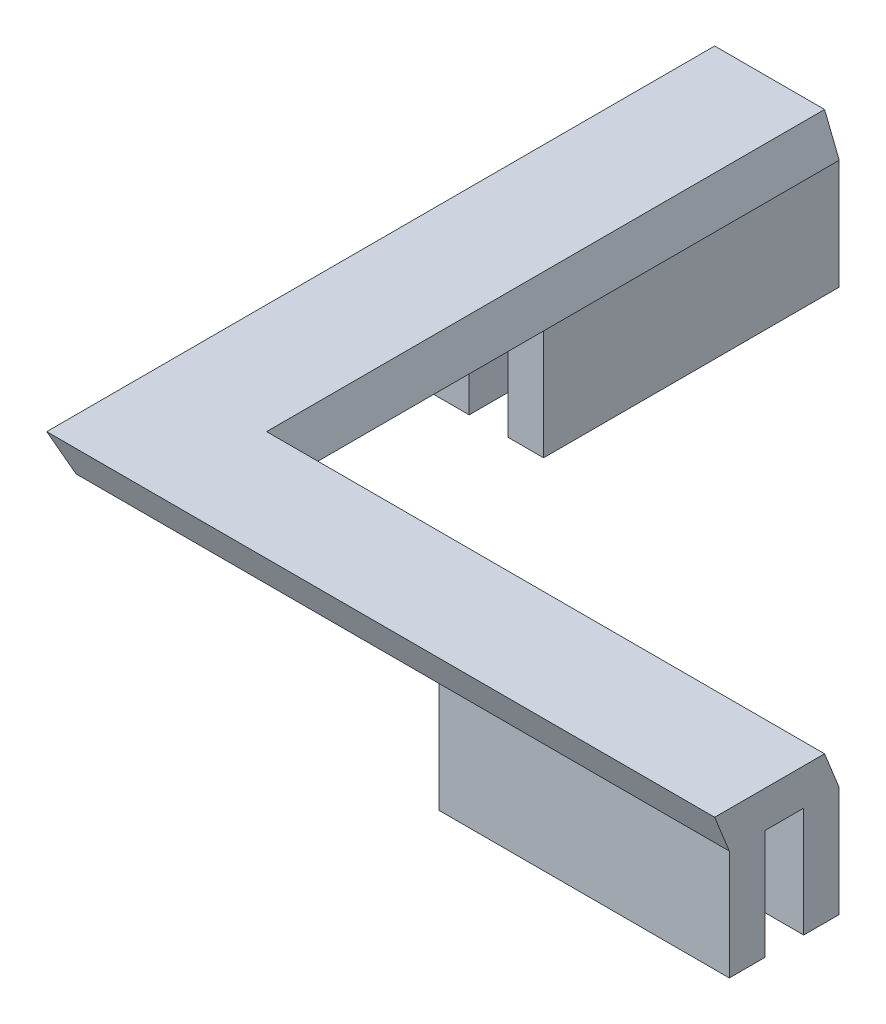
SolidWorks part; units mm, degrees
ref_plane "Front Plane" through (0, 0, 0) normal (0, 0, 1) x (1, 0, 0)
ref_plane "Top Plane" through (0, 0, 0) normal (0, 1, 0) x (1, 0, 0)
ref_plane "Right Plane" through (0, 0, 0) normal (1, 0, 0) x (0, 0, -1)
sketch "Sketch1" plane through (0, 0, 0) normal (0, 1, 0) x (1, 0, 0)
  line L1 (0, 0) -> (227.33, 0)
  line L2 (0, 0) -> (0, 225.552)
  line L3 (0, 225.552) -> (227.33, 225.552)
  line L4 (227.33, 0) -> (227.33, 225.552)
  dimension "D1" = 227.33
  dimension "D2" = 225.552
ref_plane "Plane1" through (0, 127, 0) normal (0, 1, 0) x (1, 0, 0)
sketch "Sketch2" plane through (0, 127, 0) normal (0, 1, 0) x (1, 0, 0)
  line L8 (-50.8, -50.8) -> (278.13, -50.8)
  line L9 (278.13, -50.8) -> (278.13, 276.352)
  line L10 (278.13, 276.352) -> (-50.8, 276.352)
  line L11 (-50.8, 276.352) -> (-50.8, -50.8)
  line L12 (-50.8, -50.8) -> (278.13, -50.8)
  line L13 (278.13, -50.8) -> (278.13, 276.352)
  line L14 (278.13, 276.352) -> (-50.8, 276.352)
  line L15 (-50.8, 276.352) -> (-50.8, -50.8)
  dimension "D1" = 50.8
loft "Loft1" add profiles "Sketch2" section "Sketch2" section "Sketch1"
sketch "Sketch3" plane through (0, 127, 0) normal (0, 1, 0) x (1, 0, 0)
  line L8 (-31.75, 257.302) -> (-31.75, -31.75)
  line L9 (-31.75, -31.75) -> (259.08, -31.75)
  line L10 (259.08, -31.75) -> (259.08, 257.302)
  line L11 (259.08, 257.302) -> (-31.75, 257.302)
  line L12 (-31.75, 257.302) -> (-31.75, -31.75)
  line L13 (-31.75, -31.75) -> (259.08, -31.75)
  line L14 (259.08, -31.75) -> (259.08, 257.302)
  line L15 (259.08, 257.302) -> (-31.75, 257.302)
  dimension "D1" = 19.05
sketch "Sketch4" plane through (0, 0, 0) normal (0, -1, 0) x (1, 0, 0)
  line L8 (208.28, -19.05) -> (19.05, -19.05)
  line L9 (19.05, -19.05) -> (19.05, -206.502)
  line L10 (19.05, -206.502) -> (208.28, -206.502)
  line L11 (208.28, -206.502) -> (208.28, -19.05)
  line L12 (208.28, -19.05) -> (19.05, -19.05)
  line L13 (19.05, -19.05) -> (19.05, -206.502)
  line L14 (19.05, -206.502) -> (208.28, -206.502)
  line L15 (208.28, -206.502) -> (208.28, -19.05)
  dimension "D1" = 19.05
loft "Cut-Loft3" cut profiles "Sketch3" section "Sketch4" section "Sketch3"
sketch "Sketch5" plane through (0, 0, 0) normal (0, -1, 0) x (1, 0, 0)
  line L0 (0, -61.976) -> (6.1595, -61.976)
  line L5 (0, -61.976) -> (0, -163.576)
  line L6 (0, 0) -> (0, -225.552) construction
  line L7 (6.1595, -61.976) -> (6.1595, -163.576)
  line L8 (6.1595, -163.576) -> (0, -163.576)
  line L9 (19.05, -61.976) -> (19.05, -163.576)
  line L10 (19.05, -19.05) -> (19.05, -206.502) construction
  line L11 (19.05, -61.976) -> (12.8905, -61.976)
  line L12 (12.8905, -61.976) -> (12.8905, -163.576)
  line L13 (12.8905, -163.576) -> (19.05, -163.576)
  line L14 (19.05, -19.05) -> (208.28, -206.502) construction
  line L15 (164.465, -6.1595) -> (62.865, -6.1595)
  line L16 (164.465, 0) -> (62.865, 0)
  line L17 (164.465, 0) -> (164.465, -6.1595)
  line L18 (62.865, -6.1595) -> (62.865, 0)
  line L19 (164.465, -12.8905) -> (62.865, -12.8905)
  line L20 (164.465, -19.05) -> (62.865, -19.05)
  line L21 (164.465, -19.05) -> (164.465, -12.8905)
  line L22 (62.865, -12.8905) -> (62.865, -19.05)
  line L23 (220.2815, -164.465) -> (220.2815, -62.865)
  line L24 (226.441, -164.465) -> (226.441, -62.865)
  line L25 (226.441, -164.465) -> (220.2815, -164.465)
  line L26 (220.2815, -62.865) -> (226.441, -62.865)
  line L27 (213.5505, -164.465) -> (213.5505, -62.865)
  line L28 (207.391, -164.465) -> (207.391, -62.865)
  line L29 (207.391, -164.465) -> (213.5505, -164.465)
  line L30 (213.5505, -62.865) -> (207.391, -62.865)
  line L31 (61.976, -220.2815) -> (163.576, -220.2815)
  line L32 (61.976, -226.441) -> (163.576, -226.441)
  line L33 (61.976, -226.441) -> (61.976, -220.2815)
  line L34 (163.576, -220.2815) -> (163.576, -226.441)
  line L35 (61.976, -213.5505) -> (163.576, -213.5505)
  line L36 (61.976, -207.391) -> (163.576, -207.391)
  line L37 (61.976, -207.391) -> (61.976, -213.5505)
  line L38 (163.576, -213.5505) -> (163.576, -207.391)
  line L39 (0, 0) -> (227.33, 0) construction
  point P5 (0, -112.776)
  point P12 (19.05, -112.776)
  point P14 (113.665, -112.776)
  point P46 (113.2205, -113.2205)
  dimension "D1" = 101.6
  dimension "D2" = 6.731
  dimension "D3" = 4
extrude "Boss-Extrude1" add sketch "Sketch5" along normal blind 19.05
ref_plane "Plane2" through (0, 0, -113.2205) normal (0, 0, 1) x (1, 0, 0)
sketch "Sketch6" plane through (0, 0, -113.2205) normal (0, 0, 1) x (1, 0, 0)
  line L1 (278.13, 127) -> (-54.8956, 127)
  line L2 (278.13, 127) -> (278.13, -23.8217)
  line L3 (278.13, -23.8217) -> (-54.8956, -23.8217)
  line L4 (-54.8956, 127) -> (-54.8956, -23.8217)
extrude "Cut-Extrude1" cut sketch "Sketch6" against normal blind 205.486
ref_plane "Plane3" through (113.2205, 0, 0) normal (-1, 0, 0) x (0, 0, 1)
sketch "Sketch7" plane through (113.2205, 0, 0) normal (-1, 0, 0) x (0, 0, 1)
  line L1 (-116.3268, -25.7528) -> (56.5129, -25.7528)
  line L2 (-116.3268, -25.7528) -> (-116.3268, 130.244)
  line L3 (-116.3268, 130.244) -> (56.5129, 130.244)
  line L4 (56.5129, -25.7528) -> (56.5129, 130.244)
extrude "Cut-Extrude2" cut sketch "Sketch7" against normal blind 205.486
ref_plane "Plane4" through (0, 6.35, 0) normal (0, -1, 0) x (-1, 0, 0)
sketch "Sketch8" plane through (0, 6.35, 0) normal (0, -1, 0) x (-1, 0, 0)
  line L1 (-116.3991, 116.9759) -> (65.1297, 116.9759)
  line L2 (-116.3991, 116.9759) -> (-116.3991, -66.3682)
  line L3 (-116.3991, -66.3682) -> (65.1297, -66.3682)
  line L4 (65.1297, 116.9759) -> (65.1297, -66.3682)
extrude "Cut-Extrude3" cut sketch "Sketch8" against normal blind 147.066
